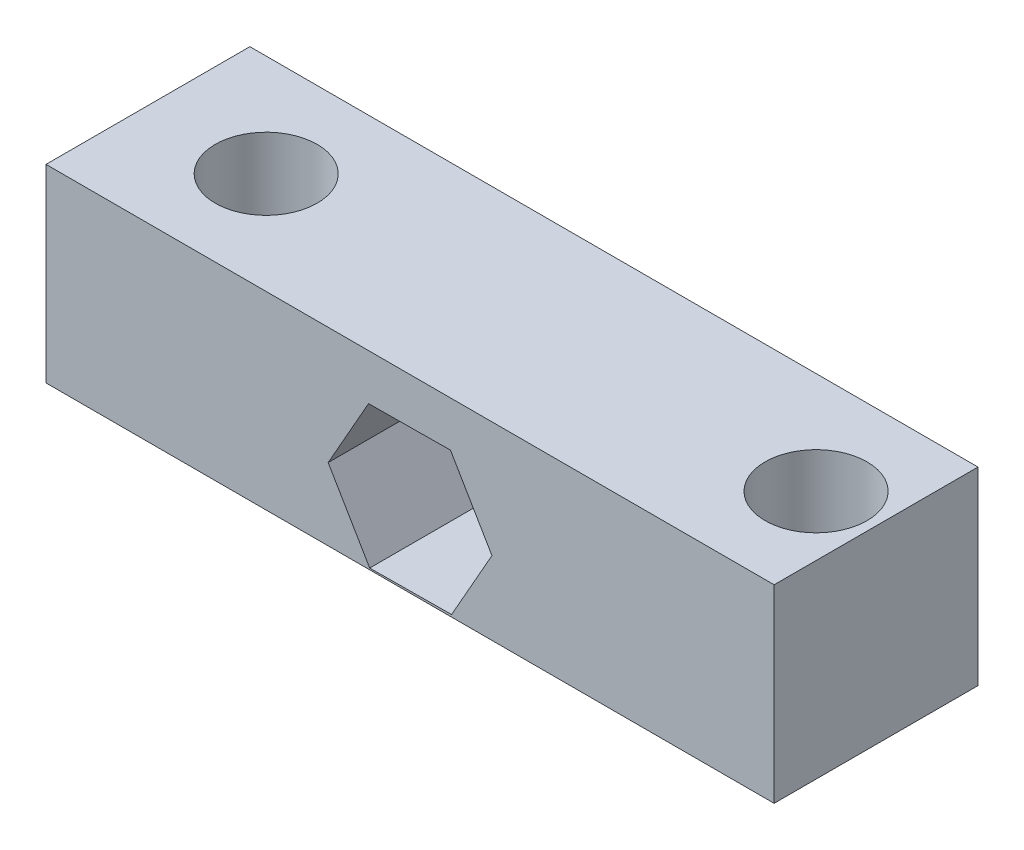
SolidWorks part; units mm, degrees
ref_plane "Front Plane" through (0, 0, 0) normal (0, 0, 1) x (1, 0, 0)
ref_plane "Top Plane" through (0, 0, 0) normal (0, 1, 0) x (1, 0, 0)
ref_plane "Right Plane" through (0, 0, 0) normal (1, 0, 0) x (0, 0, -1)
sketch "Sketch1" plane through (0, 0, 0) normal (0, 1, 0) x (1, 0, 0)
  line L0 (-55, 0) -> (55, 0) construction
  line L1 (-12.5, 3.5) -> (12.5, 3.5)
  line L2 (-12.5, 3.5) -> (-12.5, -3.5)
  line L3 (-12.5, -3.5) -> (12.5, -3.5)
  line L4 (12.5, 3.5) -> (12.5, -3.5)
  line L5 (-12.5, 3.5) -> (12.5, -3.5) construction
  line L6 (-12.5, -3.5) -> (12.5, 3.5) construction
  circle A0 centre (10.44, 0) radius 1.75
  circle A1 centre (-8.44, 0) radius 1.75
  point P0 (0, 0)
  dimension "D5" = 3.5
  dimension "D6" = 3.5
  dimension "D1" = 25
  dimension "D2" = 7
  dimension "D3" = 8.44
  dimension "D4" = 10.44
extrude "Boss-Extrude1" add sketch "Sketch1" along normal blind 6.5
sketch "Sketch3" plane through (0, 0, 0) normal (0, 0, 1) x (1, 0, 0)
  line L0 (0, -3.85) -> (0, 3.85) construction
  line L1 (1.4256, 0.0765) -> (2.8116, 2.5228)
  line L2 (2.8116, 2.5228) -> (1.386, 4.9463)
  line L3 (1.386, 4.9463) -> (-1.4256, 4.9235)
  line L4 (-1.4256, 4.9235) -> (-2.8116, 2.4772)
  line L5 (-2.8116, 2.4772) -> (-1.386, 0.0537)
  line L6 (-1.386, 0.0537) -> (1.4256, 0.0765)
  line L7 (3.85, 0) -> (-3.85, 0) construction
  circle A0 centre (0, 2.5) radius 2.435 construction
  dimension "D1" = 4.87
  dimension "D2" = 2.5
extrude "Cut-Extrude1" cut sketch "Sketch3" against normal through all both and the other way through all
